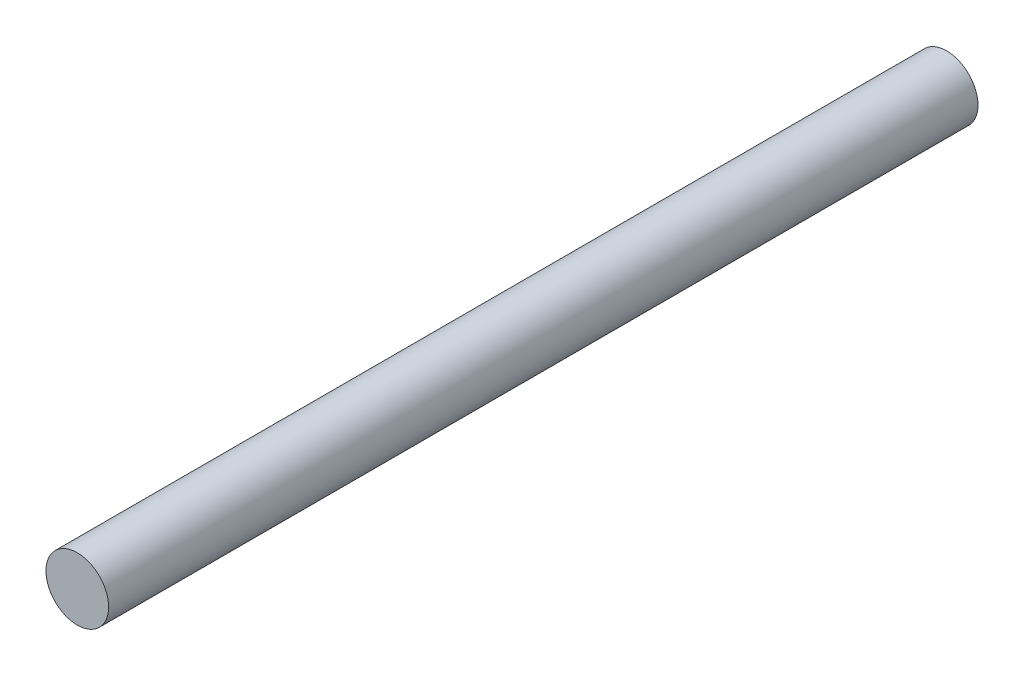
SolidWorks part; units mm, degrees
ref_plane "Front Plane" through (0, 0, 0) normal (0, 0, 1) x (1, 0, 0)
ref_plane "Top Plane" through (0, 0, 0) normal (0, 1, 0) x (1, 0, 0)
ref_plane "Right Plane" through (0, 0, 0) normal (1, 0, 0) x (0, 0, -1)
sketch "Sketch1" plane through (0, 0, 0) normal (0, 0, 1) x (1, 0, 0)
  circle A0 centre (0, 0) radius 4.7625
  dimension "D1" = 9.525
extrude "Boss-Extrude1" add sketch "Sketch1" along normal blind 132.08
